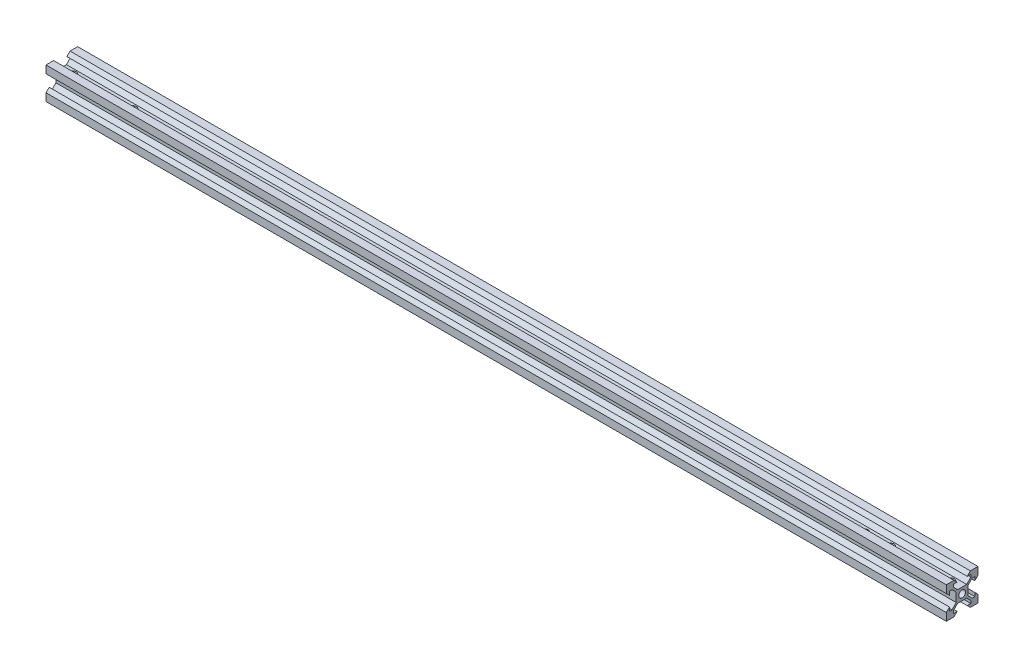
SolidWorks part; units mm, degrees
ref_plane "Front Plane" through (0, 0, 0) normal (0, 0, 1) x (1, 0, 0)
ref_plane "Top Plane" through (0, 0, 0) normal (0, 1, 0) x (1, 0, 0)
ref_plane "Right Plane" through (0, 0, 0) normal (1, 0, 0) x (0, 0, -1)
sketch "Sketch1" plane through (0, 0, 0) normal (0, 0, 1) x (1, 0, 0)
  line L0 (-284, 0) -> (284, 0)
  point P4 (0, 0)
  dimension "D1" = 568
other "20x20-ender - configured 20X20(1)"
ref_plane "Plane1" through (-284, 0, 0) normal (1, 0, 0) x (0, 1, 0)
sketch "Sketch11" plane through (-284, 0, 0) normal (1, 0, 0) x (0, 1, 0)
  line L1 (-10, 10) -> (-5.175, 10)
  line L2 (-10, 10) -> (-10, 5.175)
  line L3 (-10, -10) -> (-5.175, -10)
  line L4 (10, 10) -> (10, 5.175)
  line L7 (-8, 5.5) -> (-6.3839, 5.5)
  line L8 (-8, 5.5) -> (-8, 3.175)
  line L9 (-8, -5.5) -> (-6.3839, -5.5)
  line L10 (8, 5.5) -> (8, 3.175)
  line L11 (2.8661, -3.75) -> (5.5, -6.3839)
  line L12 (3.75, 2.8661) -> (6.3839, 5.5)
  line L13 (-5.5, 8) -> (-3.175, 8)
  line L14 (-5.5, 8) -> (-5.5, 6.3839)
  line L15 (-5.5, -8) -> (-3.175, -8)
  line L16 (5.5, 8) -> (5.5, 6.3839)
  line L17 (-6.3839, 5.5) -> (-3.75, 2.8661)
  line L18 (-3.75, -2.8661) -> (-6.3839, -5.5)
  line L19 (-2.8661, 3.75) -> (2.8661, 3.75)
  line L20 (-3.75, 2.8661) -> (-3.75, -2.8661)
  line L21 (-2.8661, -3.75) -> (2.8661, -3.75)
  line L22 (3.75, 2.8661) -> (3.75, -2.8661)
  line L23 (3.75, -2.8661) -> (6.3839, -5.5)
  line L24 (2.8661, 3.75) -> (5.5, 6.3839)
  line L25 (3.175, 8) -> (5.175, 10)
  line L26 (-3.175, 8) -> (-5.175, 10)
  line L27 (8, 3.175) -> (10, 5.175)
  line L28 (8, -3.175) -> (10, -5.175)
  line L29 (3.175, -8) -> (5.175, -10)
  line L30 (-3.175, -8) -> (-5.175, -10)
  line L31 (-8, -3.175) -> (-10, -5.175)
  line L32 (-8, 3.175) -> (-10, 5.175)
  line L33 (6.3839, 5.5) -> (8, 5.5)
  line L34 (5.5, -6.3839) -> (5.5, -8)
  line L35 (6.3839, -5.5) -> (8, -5.5)
  line L36 (-5.5, -6.3839) -> (-5.5, -8)
  line L37 (5.175, 10) -> (10, 10)
  line L38 (3.175, 8) -> (5.5, 8)
  line L39 (10, -5.175) -> (10, -10)
  line L40 (8, -3.175) -> (8, -5.5)
  line L41 (3.175, -8) -> (5.5, -8)
  line L42 (5.175, -10) -> (10, -10)
  line L43 (-10, -5.175) -> (-10, -10)
  line L44 (-8, -3.175) -> (-8, -5.5)
  line L45 (-5.5, 6.3839) -> (-2.8661, 3.75)
  line L46 (-2.8661, -3.75) -> (-5.5, -6.3839)
  line L55 (-5.175, 10) -> (5.175, 10) construction
  line L56 (10, 5.175) -> (10, -5.175) construction
  line L57 (-5.175, -10) -> (5.175, -10) construction
  line L59 (-10, 5.175) -> (-10, -5.175) construction
  circle A0 centre (0, 0) radius 2.15
  point P0 (0, 0)
  point P5 (0, 0)
  point P6 (0, 0)
  point P11 (0, 0)
  point P16 (0, 0)
  point P44 (0, 0)
  point P60 (0, 10)
  point P63 (0, 0)
  point P64 (0, -10)
  point P65 (10, 0)
  point P80 (-10, 0)
  point P82 (10, 10)
  point P83 (-10, 10)
  point P84 (-10, -10)
  point P85 (10, -10)
hole_wizard "M5x0.8 Tapped Hole1" positions "Sketch12" profile "Sketch13" tap size "M5x0.8" standard "ANSI Metric" end condition through all
sketch "Sketch12" plane through (0, 3.75, 0) normal (0, 1, 0) x (1, 0, 0)
  line L0 (284, 0) -> (277, 0) construction
  line L1 (284, 2.8661) -> (284, -2.8661) construction
  line L2 (277, 0) -> (239, 0) construction
  line L3 (0, 0) -> (0, -10) construction
  line L4 (284, -10) -> (-284, -10) construction
  point P2 (277, 0)
  point P7 (239, 0)
  point P26 (-277, 0)
  point P27 (-239, 0)
  dimension "D1" = 7
  dimension "D2" = 38
sketch "Sketch13" plane through (-239, 3.75, 0) normal (1, 0, 0) x (0, 0, 1)
  line L0 (0, 0) -> (0, 13.75)
  line L1 (0, 13.75) -> (2.1, 13.75)
  line L2 (2.1, 13.75) -> (2.1, 0)
  line L5 (2.1, 0) -> (0, 0)
  line L11 (0, -6.35) -> (0, 107.95) construction
  dimension "Thru Tap Drill Dia." = 4.2
  dimension "Thru Tap Drill Depth" = 13.75
cosmetic thread "Hole Thread1" parameters "D2"=5
cosmetic thread "Hole Thread2" parameters "D2"=5
cosmetic thread "Hole Thread3" parameters "D2"=5
cosmetic thread "Hole Thread4" parameters "D2"=5
hole_wizard "M4x0.7 Tapped Hole1" positions "Sketch14" profile "Sketch15" tap size "M4x0.7" standard "ANSI Metric" end condition through all
sketch "Sketch14" plane through (0, 3.75, 0) normal (0, 1, 0) x (1, 0, 0)
  line L0 (284, 0) -> (223, 0) construction
  line L1 (284, 2.8661) -> (284, -2.8661) construction
  point P2 (223, 0)
  dimension "D1" = 61
sketch "Sketch15" plane through (223, 3.75, 0) normal (1, 0, 0) x (0, 0, 1)
  line L0 (0, 0) -> (0, 13.75)
  line L1 (0, 13.75) -> (1.65, 13.75)
  line L2 (1.65, 13.75) -> (1.65, 0)
  line L5 (1.65, 0) -> (0, 0)
  line L11 (0, -6.35) -> (0, 107.95) construction
  dimension "Thru Tap Drill Dia." = 3.3
  dimension "Thru Tap Drill Depth" = 13.75
cosmetic thread "Hole Thread5" parameters "D2"=4
